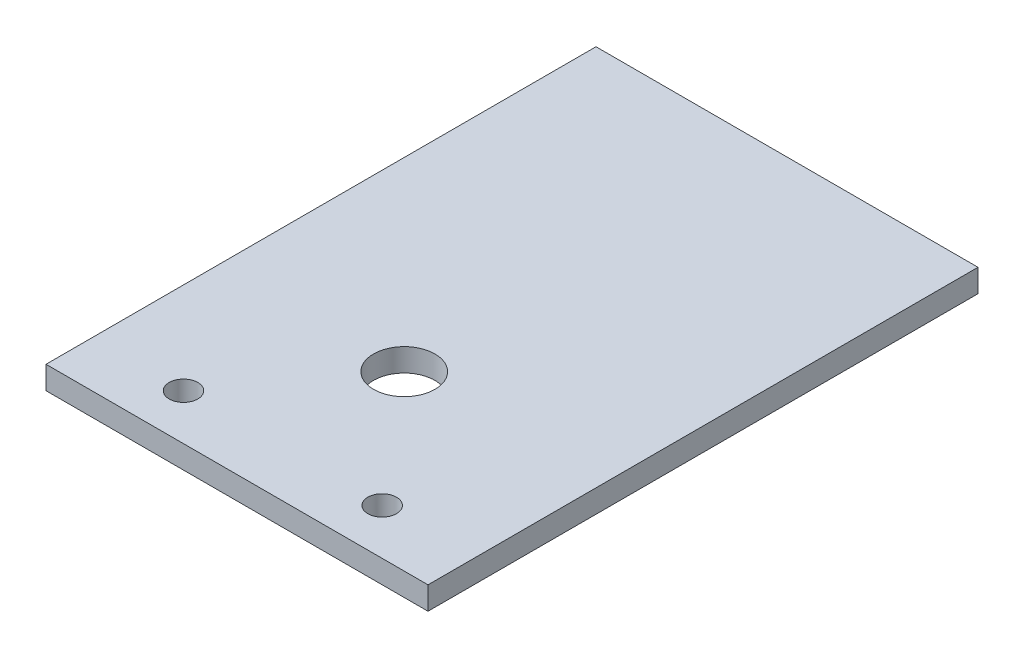
SolidWorks part; units mm, degrees
material "6061 Alloy"
ref_plane "Front Plane" through (0, 0, 0) normal (0, 0, 1) x (1, 0, 0)
ref_plane "Top Plane" through (0, 0, 0) normal (0, 1, 0) x (1, 0, 0)
ref_plane "Right Plane" through (0, 0, 0) normal (1, 0, 0) x (0, 0, -1)
sketch "Sketch1" plane through (0, 0, 0) normal (0, 1, 0) x (1, 0, 0)
  line L1 (-52.925, 76.2) -> (52.925, 76.2)
  line L2 (-52.925, 76.2) -> (-52.925, -76.2)
  line L3 (-52.925, -76.2) -> (52.925, -76.2)
  line L4 (52.925, 76.2) -> (52.925, -76.2)
  line L5 (-52.925, 76.2) -> (52.925, -76.2) construction
  line L6 (-52.925, -76.2) -> (52.925, 76.2) construction
  point P0 (0, 0)
  dimension "D1" = 152.4
  dimension "D2" = 105.85
extrude "Boss-Extrude1" add sketch "Sketch1" along normal blind 6.35
sketch "Sketch2" plane through (0, 6.35, 0) normal (0, 1, 0) x (1, 0, 0)
  line L0 (0, 0) -> (0, -11.2478) construction
  line L1 (0, 0) -> (-15.1024, 0) construction
  line L2 (-52.925, -76.2) -> (52.925, -76.2) construction
  line L3 (-52.925, 76.2) -> (-52.925, -76.2) construction
  circle A0 centre (-27.525, -63.5) radius 3.9688
  circle A1 centre (27.525, -63.5) radius 3.9688
  circle A2 centre (-1.524, -28.34) radius 8.5
  dimension "D1" = 12.7
  dimension "D2" = 25.4
  dimension "D3" = 17
  dimension "D4" = 47.86
  dimension "D5" = 51.401
extrude "Cut-Extrude1" cut sketch "Sketch2" against normal up to next
